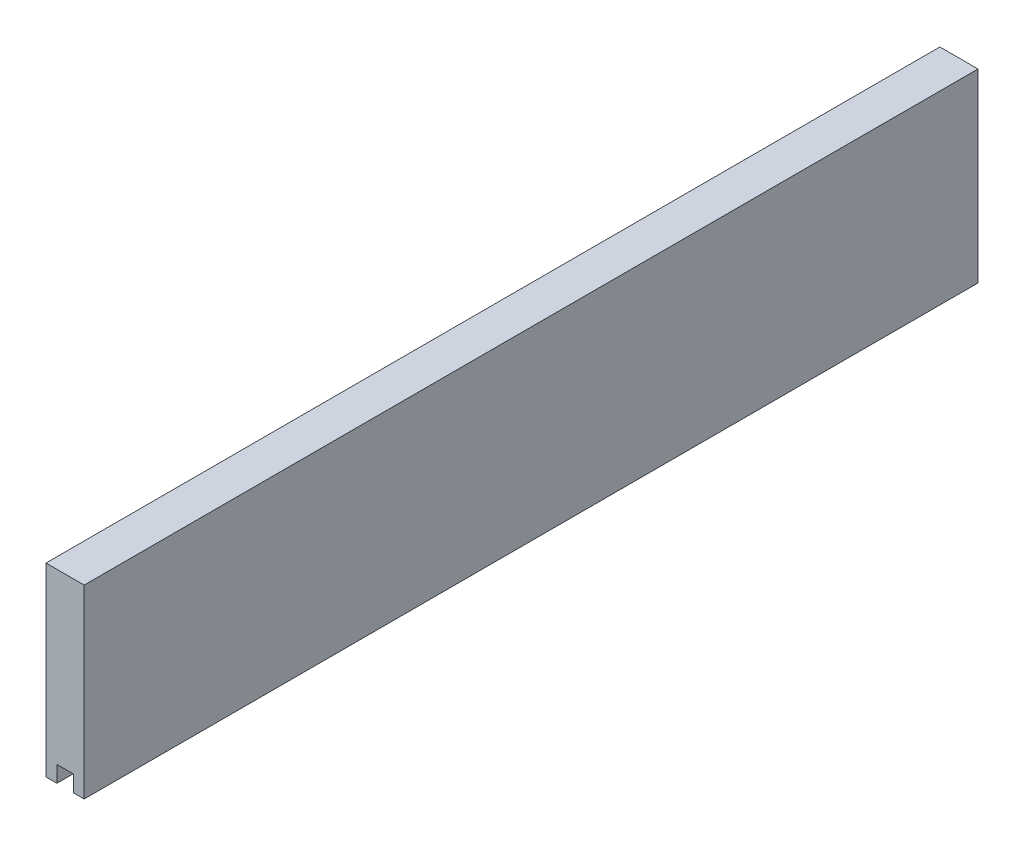
SolidWorks part; units mm, degrees
material "Сосна"
ref_plane "Спереди" through (0, 0, 0) normal (0, 0, 1) x (1, 0, 0)
ref_plane "Сверху" through (0, 0, 0) normal (0, 1, 0) x (1, 0, 0)
ref_plane "Справа" through (0, 0, 0) normal (1, 0, 0) x (0, 0, -1)
sketch "Эскиз1" plane through (0, 0, 0) normal (0, 0, 1) x (1, 0, 0)
  line L0 (0, 0) -> (0, 170)
  line L1 (0, 170) -> (35, 170)
  line L2 (35, 170) -> (35, 0)
  line L3 (35, 0) -> (25, 0)
  line L4 (25, 0) -> (25, 15)
  line L5 (25, 15) -> (10, 15)
  line L6 (10, 15) -> (10, 0)
  line L7 (10, 0) -> (0, 0)
  dimension "D1" = 170
  dimension "D2" = 35
  dimension "D3" = 10
  dimension "D4" = 15
extrude "Бобышка-Вытянуть1" add sketch "Эскиз1" against normal blind 820
